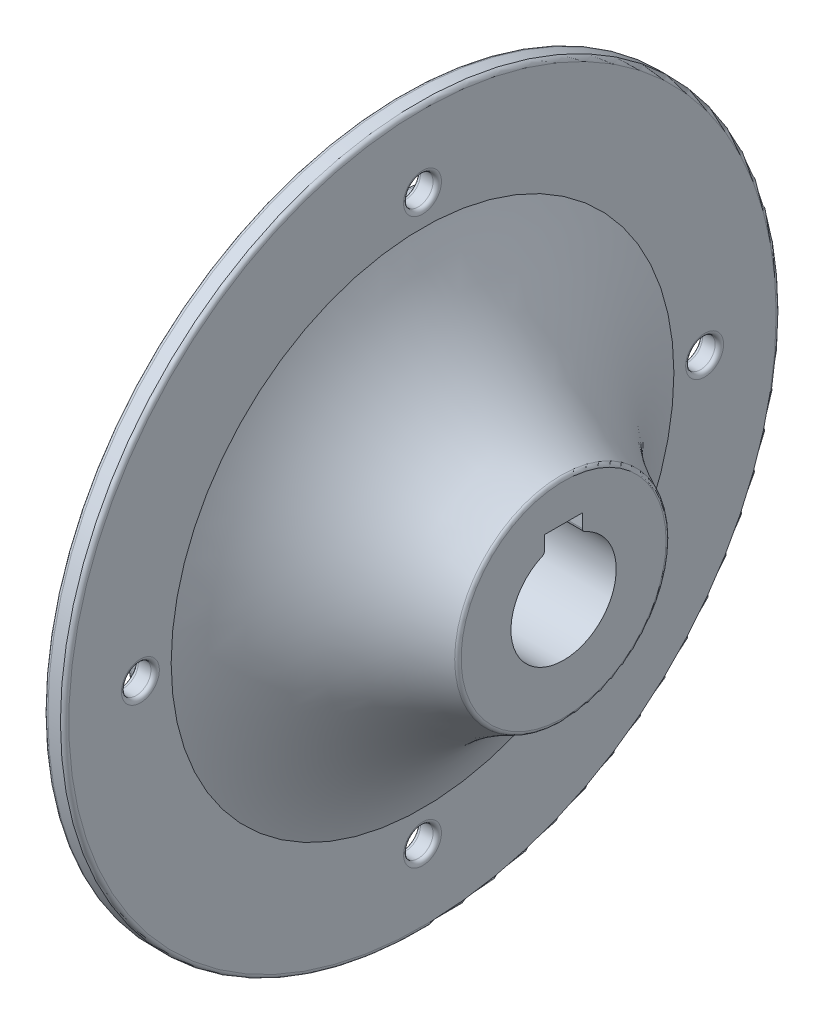
SolidWorks part; units mm, degrees
ref_plane "Front Plane" through (0, 0, 0) normal (0, 0, 1) x (1, 0, 0)
ref_plane "Top Plane" through (0, 0, 0) normal (0, 1, 0) x (1, 0, 0)
ref_plane "Right Plane" through (0, 0, 0) normal (1, 0, 0) x (0, 0, -1)
sketch "Sketch1" plane through (0, 0, 0) normal (0, 0, 1) x (1, 0, 0)
  line L0 (0, 0) -> (0, 12.65)
  line L1 (0, 12.65) -> (-3, 12.65)
  line L2 (-3, 12.65) -> (-3, 29.85)
  line L4 (19.25, 12.5) -> (19.25, 0)
  line L5 (19.25, 0) -> (0, 0)
  line L6 (-3, 29.85) -> (2.5, 29.85)
  line L7 (2.5, 29.85) -> (19.25, 12.5)
  line L8 (-0.9749, 29.85) -> (19.25, 8.9006) construction
  line L9 (0, 29.85) -> (0, 42.5)
  line L10 (0, 42.5) -> (2.5, 42.5)
  line L11 (2.5, 42.5) -> (2.5, 29.85)
  arc A0 (2.5, 29.85) -> (19.25, 12.5) centre (30.8964, 40.504) ccw
  point P12 (0, 0)
  dimension "D1" = 29.85
  dimension "D2" = 19.25
  dimension "D3" = 12.5
  dimension "D4" = 2.5
  dimension "D5" = 3
  dimension "D6" = 42.5
  dimension "D7" = 12.65
  dimension "D8" = 2.5
sketch "Sketch2" plane through (0, 0, 0) normal (0, 0, 1) x (1, 0, 0)
  line L0 (-75.1177, 0) -> (107.7478, 0) construction
revolve "Revolve1" add sketch "Sketch1" angle 360 about L0
sketch "Sketch3" plane through (0, 0, 0) normal (-1, 0, 0) x (0, 0, 1)
  line L1 (-2.4, 0) -> (2.4, 0)
  line L2 (-2.4, 0) -> (-2.4, 8.8)
  line L3 (-2.4, 8.8) -> (2.4, 8.8)
  line L4 (2.4, 0) -> (2.4, 8.8)
  circle A0 centre (0, 0) radius 6.9
  point P7 (0, 0)
  dimension "D1" = 13.8
  dimension "D2" = 8.8
  dimension "D3" = 4.8
extrude "Boss-Extrude1" add sketch "Sketch3" along normal blind 14 contours A0 L4 L3 L2 | L4 A0 L2 L1 | L2 A0 L4 L1
sketch "Sketch4" plane through (2.5, 0, 0) normal (1, 0, 0) x (0, 0, -1)
  line L0 (0, 0) -> (0, 33.5) construction
  line L1 (0, 33.5) -> (0, 42.5) construction
  circle A0 centre (0, 0) radius 42.5 construction
  circle A1 centre (0, 33.5) radius 1.75
  circle A2 centre (33.5, 0) radius 1.75
  circle A3 centre (0, -33.5) radius 1.75
  circle A4 centre (-33.5, 0) radius 1.75
  point P8 (0, 0)
  point P9 (0, 0)
  point P10 (0, 33.4704)
  point P17 (0, 0)
  dimension "D1" = 3.5
  dimension "D2" = 33.5
  dimension "D3" = 4
extrude "Cut-Extrude1" cut sketch "Sketch4" against normal through all
sketch "Sketch5" plane through (19.25, 0, 0) normal (1, 0, 0) x (0, 0, -1)
  line L1 (-2.25, 7.8) -> (2.25, 7.8)
  line L2 (-2.25, 7.8) -> (-2.25, 0)
  line L3 (-2.25, 0) -> (2.25, 0)
  line L4 (2.25, 7.8) -> (2.25, 0)
  circle A0 centre (0, 0) radius 6.25
  point P7 (0, 0)
  dimension "D1" = 12.5
  dimension "D2" = 4.5
  dimension "D3" = 7.8
extrude "Cut-Extrude2" cut sketch "Sketch5" against normal blind 23.25 contours A0 L4 L1 L2 | L4 A0 L2 L3 | L2 A0 L4 L3
sketch "Sketch6" plane through (-4, 0, 0) normal (1, 0, 0) x (0, 0, -1)
  circle A0 centre (0, 0) radius 2.25
  dimension "D1" = 4.5
extrude "Cut-Extrude3" cut sketch "Sketch6" against normal through all
fillet "Fillet1" radius 0.5 21 edges at (-14, 7.6346, -2.4) (-14, 8.8, 0) (-14, 7.6346, 2.4) (-14, -6.9, 0) (19.25, 0, 12.5) (2.5, 0, -35.25) (0, 0, -31.75) (2.5, 0, 31.75) (0, 0, 35.25) (2.5, -33.5, -1.75) (0, -33.5, 1.75) (2.5, 33.5, -1.75) (0, 33.5, 1.75) (-7, 8.8, -2.4) (-7, 8.8, 2.4) (-3, 0, 12.65) (-3, 0, 29.85) (7.625, 5.831, -2.25) (7.625, 5.831, 2.25) (0, 0, 42.5) (2.5, 0, 42.5)
